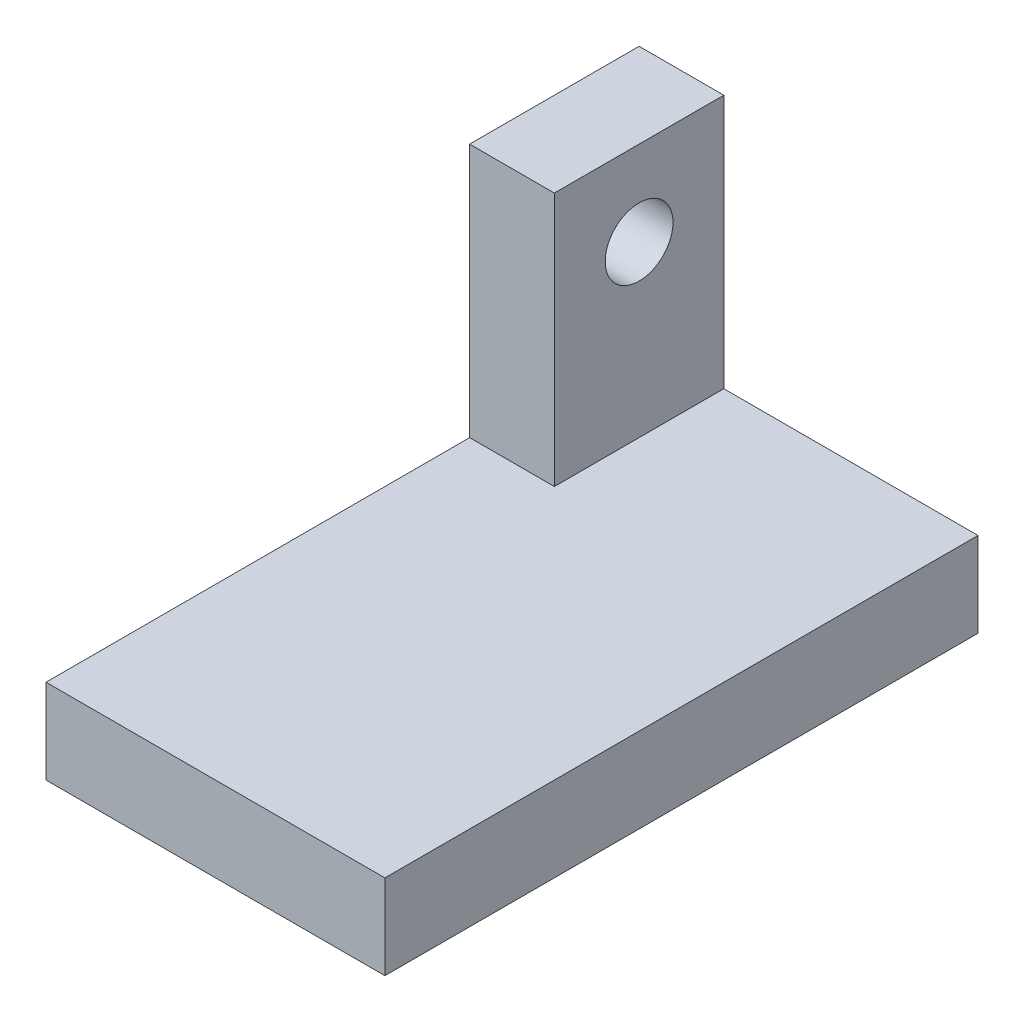
SolidWorks part; units mm, degrees
ref_plane "Front Plane" through (0, 0, 0) normal (0, 0, 1) x (1, 0, 0)
ref_plane "Top Plane" through (0, 0, 0) normal (0, 1, 0) x (1, 0, 0)
ref_plane "Right Plane" through (0, 0, 0) normal (1, 0, 0) x (0, 0, -1)
sketch "Sketch1" plane through (0, 0, 0) normal (1, 0, 0) x (0, 0, -1)
  line L1 (0, 0) -> (35, 0)
  line L2 (0, 0) -> (0, 5)
  line L3 (0, 5) -> (35, 5)
  line L4 (35, 0) -> (35, 5)
  dimension "D1" = 5
  dimension "D2" = 35
extrude "Boss-Extrude1" add sketch "Sketch1" along normal blind 20
sketch "Sketch2" plane through (0, 5, 0) normal (0, 1, 0) x (1, 0, 0)
  line L1 (0, 35) -> (5, 35)
  line L2 (0, 35) -> (0, 25)
  line L3 (0, 25) -> (5, 25)
  line L4 (5, 35) -> (5, 25)
  dimension "D1" = 10
  dimension "D2" = 5
extrude "Boss-Extrude2" add sketch "Sketch2" along normal blind 15
sketch "Sketch3" plane through (0, 0, 0) normal (0, -1, 0) x (1, 0, 0)
  line L1 (0, -35) -> (5, -35)
  line L2 (0, -35) -> (0, -25)
  line L3 (0, -25) -> (5, -25)
  line L4 (5, -35) -> (5, -25)
  dimension "D1" = 10
  dimension "D2" = 5
extrude "Boss-Extrude3" add sketch "Sketch3" along normal blind 15
sketch "Sketch4" plane through (5, 0, 0) normal (1, 0, 0) x (0, 0, -1)
  line L0 (25, 20) -> (35, 20) construction
  circle A0 centre (30, 15) radius 2
  circle A1 centre (30, -10) radius 2
  dimension "D1" = 4
  dimension "D2" = 4
  dimension "D4" = 5
  dimension "D3" = 5
extrude "Cut-Extrude1" cut sketch "Sketch4" against normal blind 15
